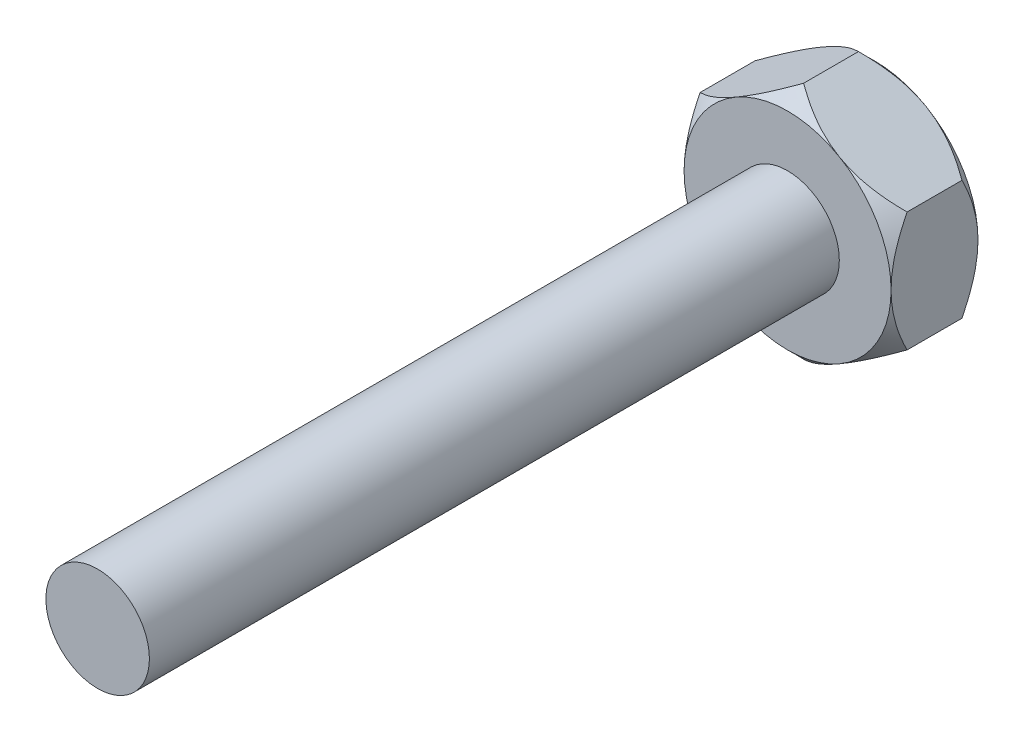
SolidWorks part; units mm, degrees
ref_plane "Alzado" through (0, 0, 0) normal (0, 0, 1) x (1, 0, 0)
ref_plane "Planta" through (0, 0, 0) normal (0, 1, 0) x (1, 0, 0)
ref_plane "Vista lateral" through (0, 0, 0) normal (1, 0, 0) x (0, 0, -1)
sketch "Sketch1" plane through (0, 0, 0) normal (0, 0, 1) x (1, 0, 0)
  circle A0 centre (0, 0) radius 1.5
extrude "Boss-Extrude1" add sketch "Sketch1" along normal blind 20
sketch "Sketch6" plane through (0, 0, 0) normal (0, 0, -1) x (-1, 0, 0)
  line L2 (0, -3.4641) -> (3, -1.7321)
  line L3 (3, -1.7321) -> (3, 1.7321)
  line L4 (3, 1.7321) -> (0, 3.4641)
  line L5 (0, 3.4641) -> (-3, 1.7321)
  line L6 (-3, 1.7321) -> (-3, -1.7321)
  line L7 (-3, -1.7321) -> (0, -3.4641)
  circle A0 centre (0, 0) radius 3 construction
extrude "Boss-Extrude3" add sketch "Sketch6" along normal blind 2.52
sketch "Sketch7" plane through (0, 0, -2.52) normal (0, 0, -1) x (-1, 0, 0)
  circle A0 centre (0, 0) radius 3
extrude "Cut-Extrude3" cut sketch "Sketch7" against normal through all draft 45 flip side to cut
sketch "Sketch8" plane through (0, 0, 0) normal (0, 0, 1) x (1, 0, 0)
  circle A0 centre (0, 0) radius 3
extrude "Cut-Extrude5" cut sketch "Sketch8" against normal through all draft 45 flip side to cut
